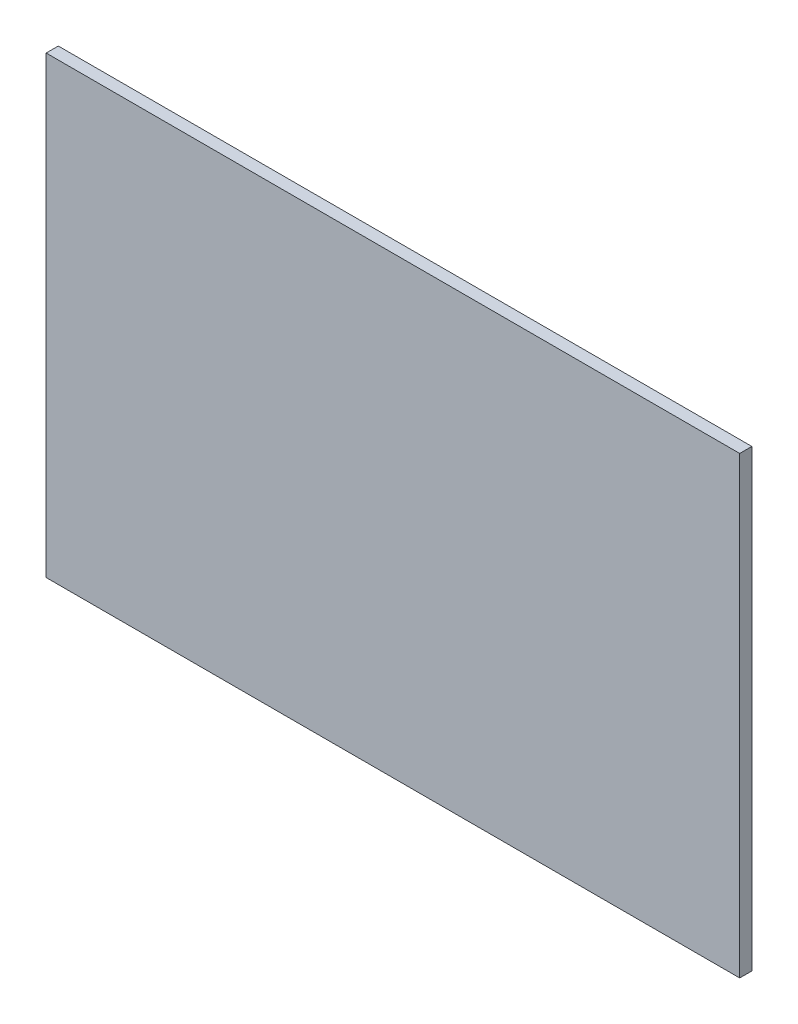
SolidWorks part; units mm, degrees
ref_plane "Front Plane" through (0, 0, 0) normal (0, 0, 1) x (1, 0, 0)
ref_plane "Top Plane" through (0, 0, 0) normal (0, 1, 0) x (1, 0, 0)
ref_plane "Right Plane" through (0, 0, 0) normal (1, 0, 0) x (0, 0, -1)
sketch "Sketch1" plane through (0, 0, 0) normal (0, 0, 1) x (1, 0, 0)
  line L1 (-83.687, 35.9628) -> (61.347, 35.9628)
  line L2 (-83.687, 35.9628) -> (-83.687, -59.0332)
  line L3 (-83.687, -59.0332) -> (61.347, -59.0332)
  line L4 (61.347, 35.9628) -> (61.347, -59.0332)
  dimension "D1" = 94.996
  dimension "D2" = 145.034
extrude "Boss-Extrude1" add sketch "Sketch1" against normal blind 2.54 contours L2 L1 L4 L3
